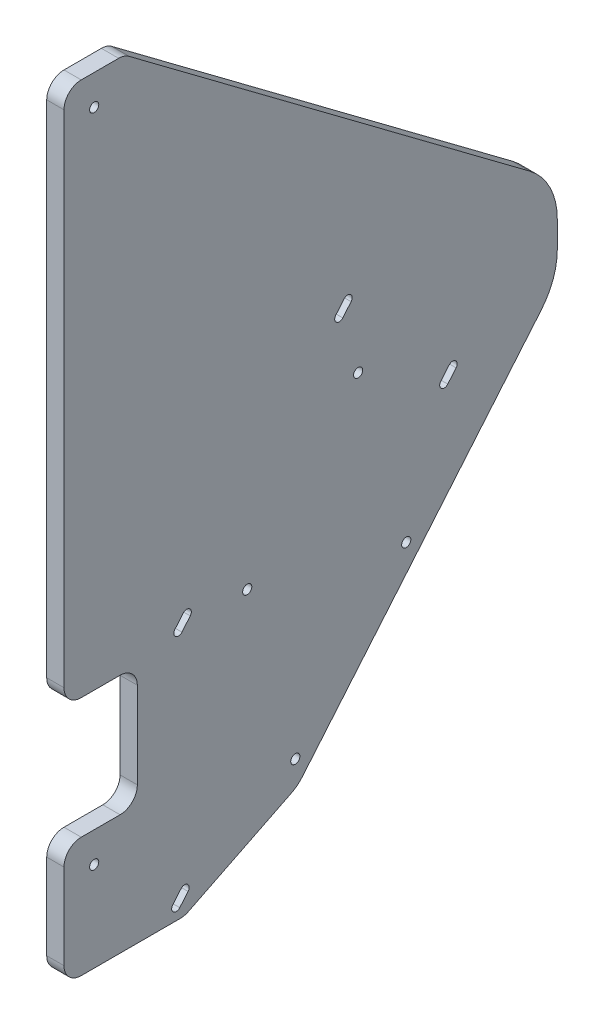
SolidWorks part; units mm, degrees
material "PE High Density"
ref_plane "Front Plane" through (0, 0, 0) normal (0, 0, 1) x (1, 0, 0)
ref_plane "Top Plane" through (0, 0, 0) normal (0, 1, 0) x (1, 0, 0)
ref_plane "Right Plane" through (0, 0, 0) normal (1, 0, 0) x (0, 0, -1)
sketch "Sketch1" plane through (0, 0, 0) normal (1, 0, 0) x (0, 0, -1)
  line L25 (0, -12.7) -> (0, -381)
  line L26 (12.7, 0) -> (40.2248, 0)
  line L27 (12.7, -393.7) -> (41.275, -393.7)
  line L28 (53.975, -406.4) -> (53.975, -469.9)
  line L29 (41.275, -482.6) -> (12.7, -482.6)
  line L30 (0, -495.3) -> (0, -558.1425)
  line L34 (363.0018, -570.8425) -> (363.0018, -150.9271) construction
  line L35 (363.0018, -150.9271) -> (44.45, 0) construction
  line L36 (87.2769, -383.159) -> (205.646, -242.0925) construction
  line L37 (87.2769, -383.159) -> (116.4632, -407.6492) construction
  line L38 (205.646, -242.0925) -> (234.8323, -266.5827) construction
  line L39 (116.4632, -407.6492) -> (234.8323, -266.5827) construction
  line L40 (85.6767, -557.944) -> (282.9052, -322.8975) construction
  line L41 (85.6767, -557.944) -> (112.4308, -580.3934) construction
  line L42 (282.9052, -322.8975) -> (309.6592, -345.3469) construction
  line L43 (112.4308, -580.3934) -> (309.6592, -345.3469) construction
  line L44 (363.0018, -570.8425) -> (0, -570.8425) construction
  line L45 (12.7, -570.8425) -> (85.6767, -570.8425)
  line L47 (180.1086, -519.8049) -> (261.7429, -422.5175)
  line L48 (261.7429, -422.5175) -> (351.1168, -316.0064)
  line L49 (363.0018, -283.3526) -> (363.0018, -263.7789)
  line L50 (342.6351, -223.1039) -> (47.8331, -2.5313)
  line L51 (180.1086, -519.8049) -> (175.4254, -525.3861)
  line L52 (167.0953, -531.9404) -> (91.4103, -569.4981)
  line L53 (84.2157, -386.8073) -> (90.3382, -379.5107) construction
  line L54 (81.6315, -384.6389) -> (87.754, -377.3423)
  line L55 (86.7999, -388.9757) -> (92.9224, -381.6791)
  line L56 (208.7073, -238.4442) -> (202.5847, -245.7408) construction
  line L57 (211.2915, -240.6126) -> (205.1689, -247.9092)
  line L58 (206.1231, -236.2758) -> (200.0005, -243.5724)
  line L59 (285.9665, -319.2492) -> (279.8439, -326.5458) construction
  line L60 (288.5507, -321.4176) -> (282.4281, -328.7142)
  line L61 (283.3823, -317.0808) -> (277.2597, -324.3774)
  line L62 (82.6155, -561.5923) -> (88.738, -554.2957) construction
  line L63 (80.0313, -559.4239) -> (86.1538, -552.1273)
  line L64 (85.1997, -563.7607) -> (91.3222, -556.4642)
  circle A31 centre (22.225, -22.225) radius 3.3734
  circle A32 centre (22.225, -504.825) radius 3.3734
  circle A37 centre (216.4646, -288.4724) radius 3.3734
  circle A38 centre (134.8309, -385.7595) radius 3.3734
  circle A39 centre (170.2279, -511.5139) radius 3.3734
  circle A40 centre (251.8621, -414.2265) radius 3.3734
  circle A41 centre (85.6767, -557.944) radius 12.8984 construction
  circle A42 centre (170.2279, -511.5139) radius 12.8984 construction
  circle A43 centre (251.8621, -414.2265) radius 12.8984 construction
  arc A46 (351.1168, -316.0064) -> (363.0018, -283.3526) centre (312.2018, -283.3526) ccw
  arc A47 (363.0018, -263.7789) -> (342.6351, -223.1039) centre (312.2018, -263.7789) ccw
  arc A48 (40.2248, 0) -> (47.8331, -2.5313) centre (40.2248, -12.7) cw
  arc A49 (0, -12.7) -> (12.7, 0) centre (12.7, -12.7) cw
  arc A50 (0, -381) -> (12.7, -393.7) centre (12.7, -381) ccw
  arc A51 (41.275, -393.7) -> (53.975, -406.4) centre (41.275, -406.4) cw
  arc A52 (53.975, -469.9) -> (41.275, -482.6) centre (41.275, -469.9) cw
  arc A53 (12.7, -482.6) -> (0, -495.3) centre (12.7, -495.3) ccw
  arc A54 (0, -558.1425) -> (12.7, -570.8425) centre (12.7, -558.1425) ccw
  arc A55 (175.4254, -525.3861) -> (167.0953, -531.9404) centre (155.5788, -508.7327) cw
  arc A56 (85.6767, -570.8425) -> (91.4103, -569.4981) centre (85.6767, -557.944) ccw
  arc A57 (81.6315, -384.6389) -> (86.7999, -388.9757) centre (84.2157, -386.8073) ccw
  arc A58 (92.9224, -381.6791) -> (87.754, -377.3423) centre (90.3382, -379.5107) ccw
  arc A59 (211.2915, -240.6126) -> (206.1231, -236.2758) centre (208.7073, -238.4442) ccw
  arc A60 (200.0005, -243.5724) -> (205.1689, -247.9092) centre (202.5847, -245.7408) ccw
  arc A61 (288.5507, -321.4176) -> (283.3823, -317.0808) centre (285.9665, -319.2492) ccw
  arc A62 (277.2597, -324.3774) -> (282.4281, -328.7142) centre (279.8439, -326.5458) ccw
  arc A63 (80.0313, -559.4239) -> (85.1997, -563.7607) centre (82.6155, -561.5923) ccw
  arc A64 (91.3222, -556.4642) -> (86.1538, -552.1273) centre (88.738, -554.2957) ccw
  point P45 (363.0018, -301.8424)
  point P48 (363.0018, -238.3424)
  point P54 (0, 0)
  point P57 (0, -393.7)
  point P60 (53.975, -393.7)
  point P63 (53.975, -482.6)
  point P73 (171.9452, -529.5337)
  point P75 (87.2769, -383.159)
  point P80 (205.646, -242.0925)
  point P85 (282.9052, -322.8975)
  point P92 (85.6767, -557.944)
  dimension "D1" = 393.7
  dimension "D8" = 22.225
  dimension "D10" = 6.7469
  dimension "D11" = 22.225
  dimension "D12" = 242.0925
  dimension "D17" = 85.6767
  dimension "D19" = 282.9052
  dimension "D20" = 322.8975
  dimension "D29" = 25.7969
  dimension "D30" = 12.7
  dimension "D31" = 12.7
  dimension "D28" = 50.8
  dimension "D33" = 9.525
  dimension "D34" = 3.3734
  dimension "D27" = 63.5
  dimension "D36" = 6.7469
  dimension "D37" = 9.525
  dimension "D38" = 9.525
  dimension "D7" = 22.225
  dimension "D9" = 6.7469
  dimension "D14" = 9.525
  dimension "D15" = 87.2769
  dimension "D22" = 28.575
  dimension "D25" = 89.916
  dimension "D26" = 127
  dimension "D4" = 419.9153
  dimension "D32" = 25.908
  dimension "D35" = 6.7469
  dimension "D2" = 53.975
  dimension "D3" = 88.9
  dimension "D5" = 44.45
  dimension "D6" = 352.4972
  dimension "D13" = 205.646
  dimension "D16" = 383.159
  dimension "D18" = 557.944
  dimension "D21" = 38.1
  dimension "D23" = 28.575
  dimension "D24" = 34.925
extrude "Boss-Extrude1" add sketch "Sketch1" along normal blind 12.7
